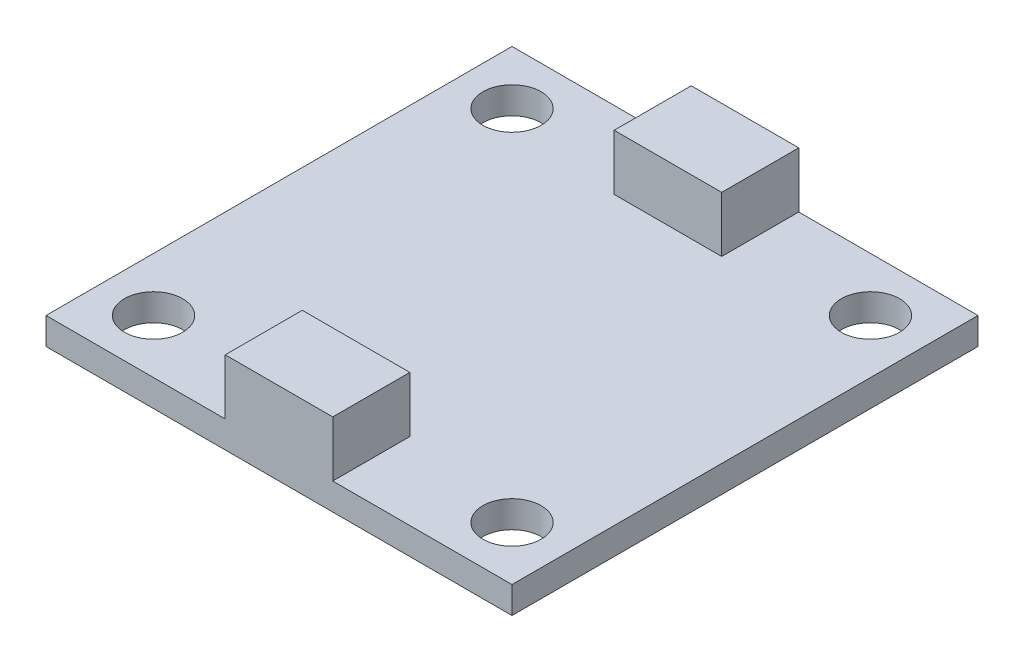
SolidWorks part; units mm, degrees
ref_plane "Front Plane" through (0, 0, 0) normal (0, 0, 1) x (1, 0, 0)
ref_plane "Top Plane" through (0, 0, 0) normal (0, 1, 0) x (1, 0, 0)
ref_plane "Right Plane" through (0, 0, 0) normal (1, 0, 0) x (0, 0, -1)
sketch "Sketch1" plane through (0, 0, 0) normal (0, 1, 0) x (1, 0, 0)
  line L1 (-13, -13) -> (13, -13)
  line L2 (-13, -13) -> (-13, 13)
  line L3 (-13, 13) -> (13, 13)
  line L4 (13, -13) -> (13, 13)
  line L5 (-13, -13) -> (13, 13) construction
  line L6 (-13, 13) -> (13, -13) construction
  point P0 (0, 0)
  dimension "D1" = 26
  dimension "D2" = 26
extrude "Boss-Extrude1" add sketch "Sketch1" along normal blind 1.5
sketch "Sketch2" plane through (0, 1.5, 0) normal (0, 1, 0) x (1, 0, 0)
  line L1 (-10, -10) -> (10, -10) construction
  line L2 (-10, -10) -> (-10, 10) construction
  line L3 (-10, 10) -> (10, 10) construction
  line L4 (10, -10) -> (10, 10) construction
  line L5 (-10, -10) -> (10, 10) construction
  line L6 (-10, 10) -> (10, -10) construction
  circle A0 centre (-10, 10) radius 1.625
  circle A1 centre (10, 10) radius 1.625
  circle A2 centre (10, -10) radius 1.625
  circle A3 centre (-10, -10) radius 1.625
  point P0 (0, 0)
  dimension "D2" = 3.25
  dimension "D1" = 20
extrude "Cut-Extrude1" cut sketch "Sketch2" against normal through all
sketch "Sketch3" plane through (0, 1.5, 0) normal (0, 1, 0) x (1, 0, 0)
  line L0 (0, 0) -> (0, 50000) construction
  line L1 (13, 13) -> (-13, 13) construction
  line L2 (-3, 8.7) -> (3, 8.7)
  line L3 (-3, 8.7) -> (-3, 13)
  line L4 (-3, 13) -> (3, 13)
  line L5 (3, 8.7) -> (3, 13)
  line L6 (-3, 8.7) -> (3, 13) construction
  line L7 (-3, 13) -> (3, 8.7) construction
  line L8 (-13, -13) -> (13, -13) construction
  line L9 (-3, -8.7) -> (3, -8.7)
  line L10 (-3, -8.7) -> (-3, -13)
  line L11 (-3, -13) -> (3, -13)
  line L12 (3, -8.7) -> (3, -13)
  line L13 (-3, -8.7) -> (3, -13) construction
  line L14 (-3, -13) -> (3, -8.7) construction
  point P3 (0, 10.85)
  point P10 (0, -10.85)
  dimension "D1" = 6
  dimension "D2" = 4.3
extrude "Boss-Extrude2" add sketch "Sketch3" along normal blind 3.1
